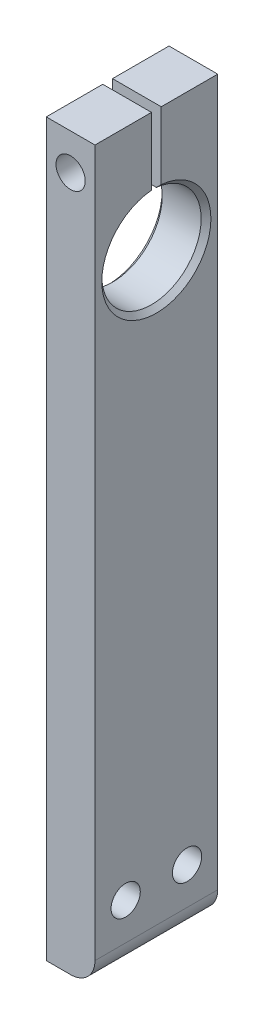
SolidWorks part; units mm, degrees
ref_plane "Front Plane" through (0, 0, 0) normal (0, 0, 1) x (1, 0, 0)
ref_plane "Top Plane" through (0, 0, 0) normal (0, 1, 0) x (1, 0, 0)
ref_plane "Right Plane" through (0, 0, 0) normal (1, 0, 0) x (0, 0, -1)
sketch "Sketch1" plane through (0, 0, 0) normal (1, 0, 0) x (0, 0, -1)
  line L0 (-12.6, -25) -> (-12.6, -125)
  line L1 (-12.6, 25) -> (12.6, 25)
  line L2 (-12.6, 25) -> (-12.6, -25)
  line L4 (12.6, 25) -> (12.6, -25)
  line L5 (-12.6, 25) -> (12.6, -25) construction
  line L6 (-12.6, -25) -> (12.6, 25) construction
  line L7 (-12.6, -125) -> (12.6, -125)
  line L8 (12.6, -125) -> (12.6, -25)
  circle A0 centre (0, 0) radius 10.2
  dimension "D1" = 25.2
  dimension "D2" = 20.4
  dimension "D3" = 50
extrude "Boss-Extrude1" add sketch "Sketch1" along normal blind 10
sketch "Sketch2" plane through (0, 0, 0) normal (1, 0, 0) x (0, 0, -1)
  circle A0 centre (-6.3, -112.4) radius 1.7
  circle A1 centre (6.3, -112.4) radius 1.7
extrude "Cut-Extrude2" cut sketch "Sketch2" along normal through all
sketch "Sketch5" plane through (0, 0, 0) normal (-1, 0, 0) x (0, 0, 1)
  line L0 (0, 0) -> (0, 25) construction
  line L2 (-12.6, 25) -> (12.6, 25) construction
  line L4 (-1, 25) -> (1, 25)
  line L5 (-1, 25) -> (-1, 0)
  line L6 (-1, 0) -> (1, 0)
  line L7 (1, 25) -> (1, 0)
  line L8 (-1, 25) -> (1, 0) construction
  line L9 (-1, 0) -> (1, 25) construction
  point P4 (0, 12.5)
  dimension "D1" = 25
  dimension "D2" = 2
extrude "Cut-Extrude4" cut sketch "Sketch5" against normal through all
sketch "Sketch7" plane through (0, 0, 12.6) normal (0, 0, 1) x (1, 0, 0)
  line L0 (5, 25) -> (5, 10.15) construction
  line L1 (10, 25) -> (0, 25) construction
  circle A0 centre (5, 17.575) radius 1.7
  dimension "D1" = 3.4
extrude "Cut-Extrude5" cut sketch "Sketch7" against normal through all
ref_plane "Plane1" through (0, 0, -4) normal (0, 0, 1) x (1, 0, 0)
sketch "Sketch8" plane through (0, 0, -4) normal (0, 0, 1) x (1, 0, 0)
  line L0 (3.2679, 20.575) -> (0, 20.575)
  line L1 (8.4641, 17.575) -> (6.7321, 20.575)
  line L2 (6.7321, 20.575) -> (3.2679, 20.575)
  line L5 (3.2679, 14.575) -> (6.7321, 14.575)
  line L6 (6.7321, 14.575) -> (8.4641, 17.575)
  line L8 (0, 25) -> (0, -125) construction
  line L9 (0, 20.575) -> (0, 14.575)
  line L10 (0, 14.575) -> (3.2679, 14.575)
  line L15 (3.2679, 20.575) -> (1.5359, 17.575) [skipped]
  line L16 (1.5359, 17.575) -> (3.2679, 14.575) [skipped]
  circle A0 centre (5, 17.575) radius 3 construction
  dimension "D1" = 6
extrude "Cut-Extrude7" cut sketch "Sketch8" against normal blind 2.5
fillet "Fillet1" radius 5 1 edges at (10, -125, 0)
chamfer "Chamfer1" distance 1 angle 45 2 edges at (0, -10.2, 0) (10, -10.2, 0)
sketch "Sketch9" plane through (0, 0, 12.6) normal (0, 0, 1) x (1, 0, 0)
  circle A0 centre (5, 17.575) radius 3
  dimension "D1" = 6
extrude "Cut-Extrude8" cut sketch "Sketch9" against normal blind 8
sketch "Sketch13" plane through (10, 0, 0) normal (1, 0, 0) x (0, 0, -1)
  circle A0 centre (6.3, -112.4) radius 3
  circle A1 centre (-6.3, -112.4) radius 3
  dimension "D1" = 6
  dimension "D2" = 6
extrude "Cut-Extrude9" cut sketch "Sketch13" against normal blind 5
